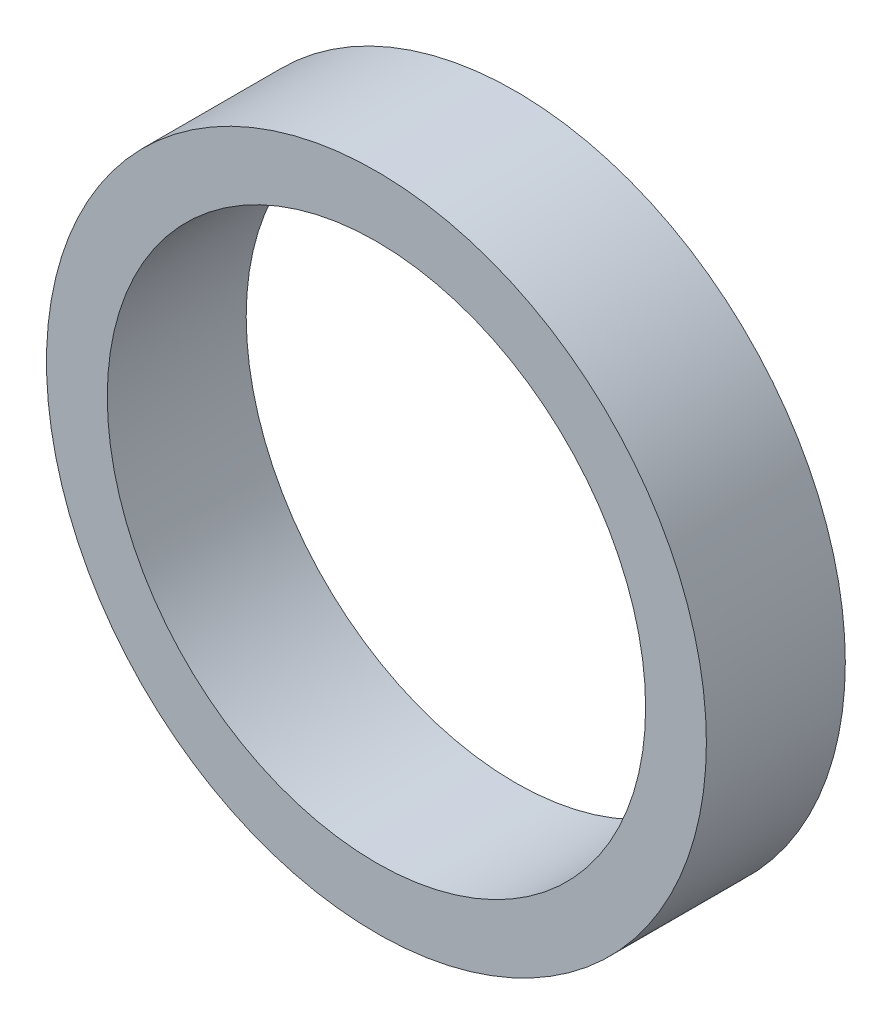
SolidWorks part; units mm, degrees
ref_plane "Front" through (0, 0, 0) normal (0, 0, 1) x (1, 0, 0)
ref_plane "Top" through (0, 0, 0) normal (0, 1, 0) x (1, 0, 0)
ref_plane "Right" through (0, 0, 0) normal (1, 0, 0) x (0, 0, -1)
sketch "Esquisse1" plane through (0, 0, 0) normal (0, 0, 1) x (1, 0, 0)
  circle A0 centre (0, 0) radius 15.5
  circle A1 centre (0, 0) radius 19
  dimension "D1" = 31
  dimension "D2" = 38
extrude "Boss.-Extru.1" add sketch "Esquisse1" along normal blind 8
